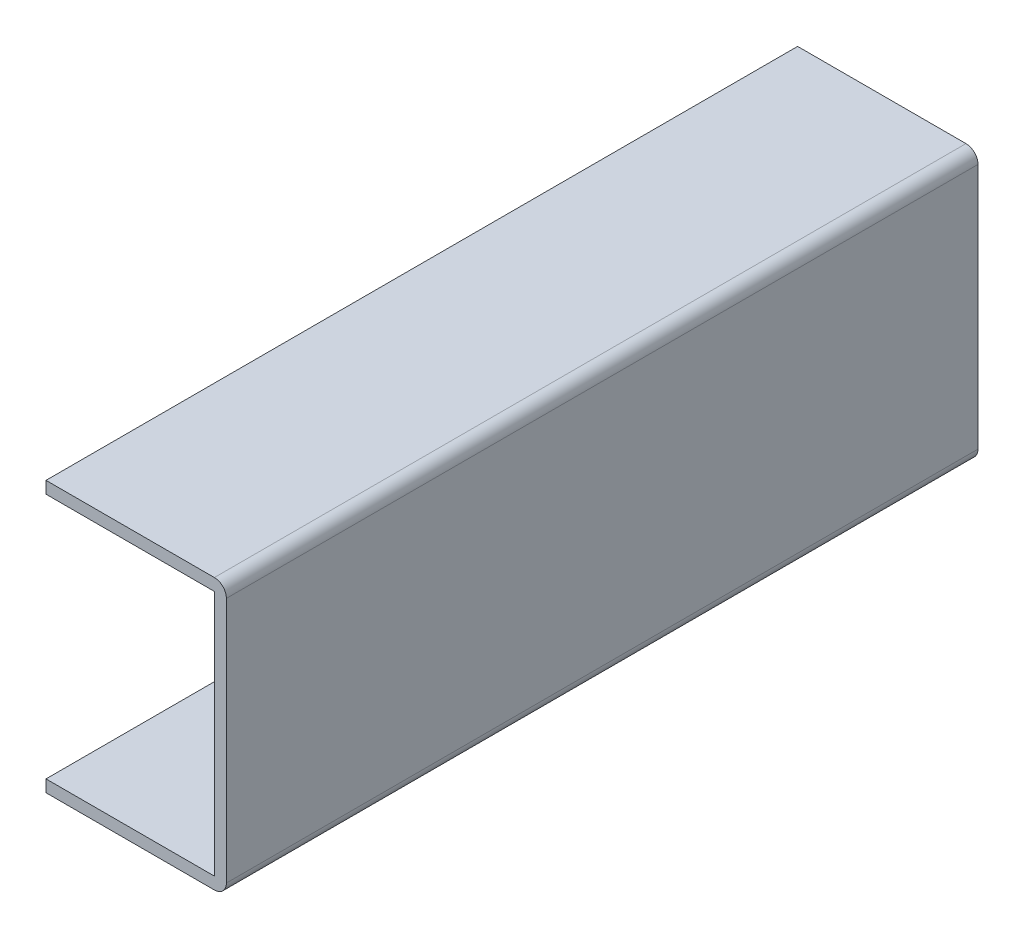
SolidWorks part; units mm, degrees
ref_plane "Plano frontal" through (0, 0, 0) normal (0, 0, 1) x (1, 0, 0)
ref_plane "Plano superior" through (0, 0, 0) normal (0, 1, 0) x (1, 0, 0)
ref_plane "Plano direito" through (0, 0, 0) normal (1, 0, 0) x (0, 0, -1)
sketch "Esboço1" plane through (0, 0, 0) normal (0, 0, 1) x (1, 0, 0)
  line L0 (-8.0121, -28.7518) -> (-7.7321, -28.7518)
  line L1 (-7.7321, -28.7518) -> (-7.7321, -29.1618)
  line L2 (-7.7321, -29.1618) -> (-8.0121, -29.1618)
  line L3 (-8.0121, -29.1618) -> (-8.0121, -29.1818)
  line L4 (-8.0121, -29.1818) -> (-7.7121, -29.1818)
  line L5 (-7.7121, -29.1818) -> (-7.7121, -28.7318)
  line L6 (-7.7121, -28.7318) -> (-8.0121, -28.7318)
  line L7 (-8.0121, -28.7318) -> (-8.0121, -28.7518)
  dimension "D2" = 0.28
  dimension "D3" = 0.3
  dimension "D4" = 0.41
extrude "Ressalto-extrusão1" add sketch "Esboço1" along normal blind 1.25
fillet "Filete1" radius 0.02 1 edges at (-7.7121, -28.7318, 0.625)
fillet "Filete2" radius 0.02 1 edges at (-7.7121, -29.1818, 0.625)
